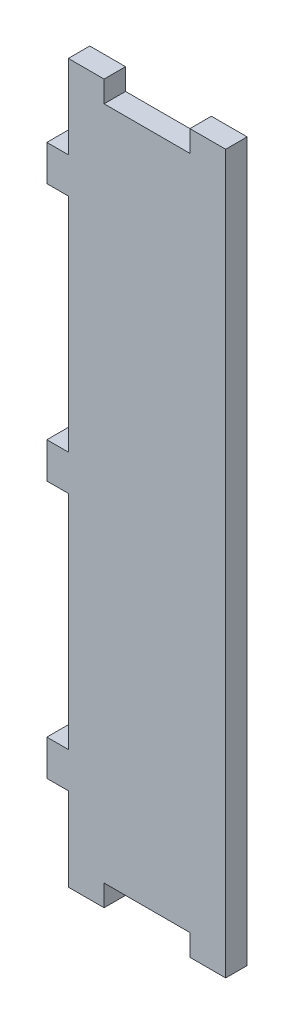
SolidWorks part; units mm, degrees
ref_plane "Plan de face" through (0, 0, 0) normal (0, 0, 1) x (1, 0, 0)
ref_plane "Plan de dessus" through (0, 0, 0) normal (0, 1, 0) x (1, 0, 0)
ref_plane "Plan de droite" through (0, 0, 0) normal (1, 0, 0) x (0, 0, -1)
sketch "Esquisse1" plane through (0, 0, 0) normal (0, 0, 1) x (1, 0, 0)
  line L1 (0, -18) -> (150, -18)
  line L2 (0, -18) -> (0, 584)
  line L3 (0, 584) -> (150, 584)
  line L4 (150, -18) -> (150, 584)
extrude "Boss.-Extru.1" add sketch "Esquisse1" against normal blind 18
sketch "Esquisse2" plane through (0, 0, 0) normal (0, 0, 1) x (1, 0, 0)
  line L0 (0, 584) -> (0, -18) construction
  line L1 (0, 584) -> (18, 584)
  line L2 (0, 584) -> (0, 514)
  line L3 (0, 514) -> (18, 514)
  line L4 (18, 584) -> (18, 514)
  line L5 (150, 584) -> (0, 584) construction
  line L6 (18, 514) -> (18, 484) construction
  line L7 (0, 484) -> (18, 484)
  line L8 (0, 484) -> (0, 298)
  line L9 (0, 298) -> (18, 298)
  line L10 (18, 484) -> (18, 298)
  line L11 (0, 268) -> (18, 268)
  line L12 (0, 268) -> (0, 82)
  line L13 (0, 82) -> (18, 82)
  line L14 (18, 268) -> (18, 82)
  line L15 (0, -18) -> (18, -18)
  line L16 (0, -18) -> (0, 52)
  line L17 (0, 52) -> (18, 52)
  line L18 (18, -18) -> (18, 52)
  line L19 (18, 298) -> (18, 268) construction
  line L20 (18, 52) -> (18, 82) construction
  line L21 (0, 283) -> (18, 283) construction
  dimension "D1" = 18
  dimension "D2" = 30
  dimension "D3" = 70
extrude "Enlèv. mat.-Extru.1" cut sketch "Esquisse2" against normal through all
sketch "Esquisse3" plane through (0, 0, 0) normal (0, 0, 1) x (1, 0, 0)
  line L0 (150, 584) -> (18, 584) construction
  line L1 (48, 584) -> (120, 584)
  line L2 (48, 584) -> (48, 566)
  line L3 (48, 566) -> (120, 566)
  line L4 (120, 584) -> (120, 566)
  line L5 (18, 566) -> (0, 566) construction
  line L6 (18, -18) -> (150, -18) construction
  line L7 (48, -18) -> (120, -18)
  line L8 (48, -18) -> (48, 0)
  line L9 (48, 0) -> (120, 0)
  line L10 (120, -18) -> (120, 0)
  line L11 (150, 0) -> (0, 0) construction
  line L12 (18, 514) -> (18, 584) construction
  point P16 (84, 584)
  line M4 (18, -18) -> (150, -18)
  line M6 (150, 584) -> (18, 584)
  dimension "D1" = 30
extrude "Enlèv. mat.-Extru.2" cut sketch "Esquisse3" against normal through all contours L4 L2 L3 M6 | L10 L9 L8 M4
